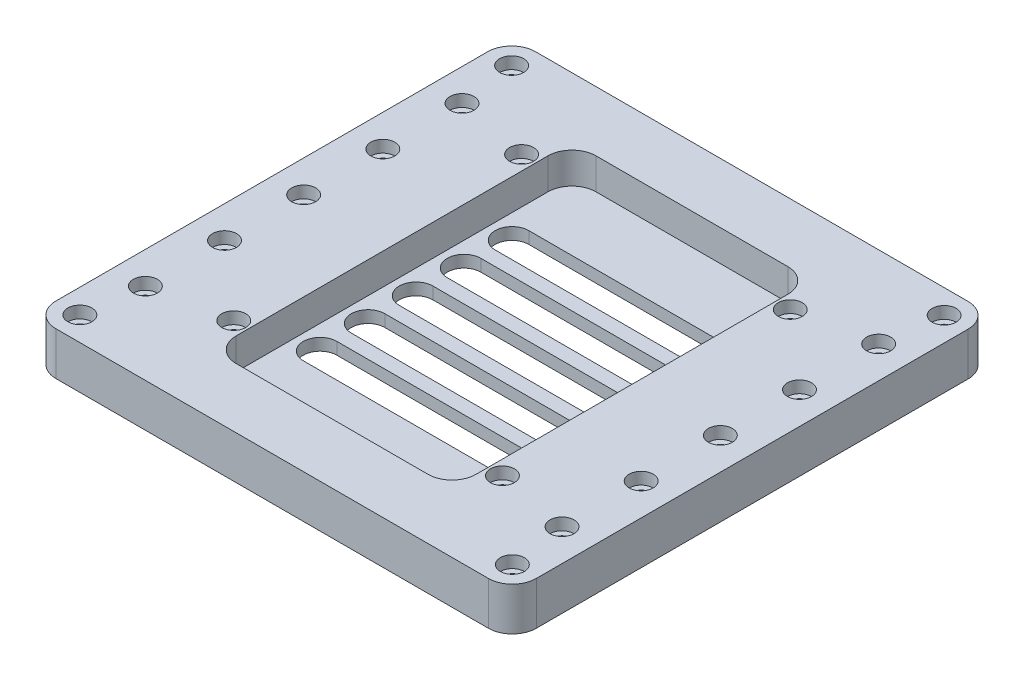
SolidWorks part; units mm, degrees
ref_plane "前视基准面" through (0, 0, 0) normal (0, 0, 1) x (1, 0, 0)
ref_plane "上视基准面" through (0, 0, 0) normal (0, 1, 0) x (1, 0, 0)
ref_plane "右视基准面" through (0, 0, 0) normal (1, 0, 0) x (0, 0, -1)
sketch "Sketch1" plane through (0, 0, 0) normal (0, 1, 0) x (1, 0, 0)
  line L0 (83.75, 0) -> (89.95, 0) construction
  line L1 (-100.15, 100) -> (100.15, 100)
  line L2 (-100.15, 100) -> (-100.15, -100)
  line L3 (-100.15, -100) -> (100.15, -100)
  line L4 (100.15, 100) -> (100.15, -100)
  line L5 (-100.15, 100) -> (100.15, -100) construction
  line L6 (-100.15, -100) -> (100.15, 100) construction
  line L7 (86.85, 75) -> (86.85, -75) construction
  line L8 (0, 0) -> (0, -34.4802) construction
  line L9 (0, 0) -> (-31.4397, 0) construction
  line L10 (56, 60) -> (-56, 60) construction
  line L11 (56, 60) -> (56, -60) construction
  line L12 (56, -60) -> (-56, -60) construction
  line L13 (-56, 60) -> (-56, -60) construction
  line L14 (56, 60) -> (-56, -60) construction
  line L15 (56, -60) -> (-56, 60) construction
  line L16 (100.15, 0) -> (86.85, 0) construction
  line L17 (0, 0) -> (0, 40) construction
  line L18 (0, 40) -> (40, 40) construction
  line L19 (40, 33) -> (-40, 33)
  line L20 (40, 47) -> (-40, 47)
  line L21 (40, 13) -> (-40, 13)
  line L22 (40, 27) -> (-40, 27)
  line L23 (40, -7) -> (-40, -7)
  line L24 (40, 7) -> (-40, 7)
  line L25 (40, -27) -> (-40, -27)
  line L26 (40, -13) -> (-40, -13)
  line L27 (40, -47) -> (-40, -47)
  line L28 (40, -33) -> (-40, -33)
  circle A0 centre (86.85, 0) radius 2.5
  circle A1 centre (86.85, 33) radius 2.5
  circle A2 centre (86.85, 66) radius 2.5
  circle A3 centre (86.85, -66) radius 2.5
  circle A4 centre (86.85, -33) radius 2.5
  circle A5 centre (-86.85, 66) radius 2.5
  circle A6 centre (-86.85, 33) radius 2.5
  circle A7 centre (-86.85, 0) radius 2.5
  circle A8 centre (-86.85, -33) radius 2.5
  circle A9 centre (-86.85, -66) radius 2.5
  circle A10 centre (56, -60) radius 2.5
  circle A11 centre (-56, -60) radius 2.5
  circle A12 centre (-56, 60) radius 2.5
  circle A13 centre (56, 60) radius 2.5
  arc A15 (40, 33) -> (40, 47) centre (40, 40) ccw
  arc A16 (-40, 33) -> (-40, 47) centre (-40, 40) cw
  arc A17 (-40, 13) -> (-40, 27) centre (-40, 20) cw
  arc A18 (40, 13) -> (40, 27) centre (40, 20) ccw
  arc A19 (-40, -7) -> (-40, 7) centre (-40, 0) cw
  arc A20 (40, -7) -> (40, 7) centre (40, 0) ccw
  arc A21 (-40, -27) -> (-40, -13) centre (-40, -20) cw
  arc A22 (40, -27) -> (40, -13) centre (40, -20) ccw
  arc A23 (-40, -47) -> (-40, -33) centre (-40, -40) cw
  arc A24 (40, -47) -> (40, -33) centre (40, -40) ccw
  point P0 (0, 0)
  point P11 (86.85, 0)
  point P50 (0, 33)
  point P52 (0, 47)
  dimension "D3" = 3
  dimension "D6" = 5
  dimension "D7" = 5
  dimension "D11" = 7
  dimension "D1" = 200.3
  dimension "D2" = 200
  dimension "D4" = 112
  dimension "D5" = 120
  dimension "D8" = 13.3
  dimension "D9" = 40
  dimension "D10" = 40
  dimension "D12" = 5
extrude "Boss-Extrude1" add sketch "Sketch1" along normal blind 18
fillet "Fillet1" radius 10 4 edges at (-100.15, 9, 100) (100.15, 9, 100) (-100.15, 9, -100) (100.15, 9, -100)
sketch "Sketch2" plane through (0, 18, 0) normal (0, 1, 0) x (1, 0, 0)
  line L0 (0, 0) -> (0, 100) construction
  line L1 (90.15, 100) -> (-90.15, 100) construction
  line L2 (0, 0) -> (-100.15, 0) construction
  line L3 (-100.15, 90) -> (-100.15, -90) construction
  circle A0 centre (-86.85, 66) radius 5
  circle A1 centre (-86.85, 33) radius 5
  circle A2 centre (-86.85, 0) radius 5
  circle A3 centre (-86.85, -33) radius 5
  circle A4 centre (-86.85, -66) radius 5
  circle A5 centre (86.85, -66) radius 5
  circle A6 centre (86.85, -33) radius 5
  circle A7 centre (86.85, 0) radius 5
  circle A8 centre (86.85, 33) radius 5
  circle A9 centre (86.85, 66) radius 5
  circle A10 centre (-56, 60) radius 5
  circle A11 centre (-56, -60) radius 5
  circle A12 centre (56, -60) radius 5
  circle A13 centre (56, 60) radius 5
  dimension "D1" = 5
  dimension "D2" = 10
  dimension "D3" = 10
  dimension "D4" = 33
extrude "Cut-Extrude1" cut sketch "Sketch2" against normal blind 5
sketch "Sketch3" plane through (0, 18, 0) normal (0, 1, 0) x (1, 0, 0)
  line L1 (-50, 75) -> (50, 75)
  line L2 (-50, 75) -> (-50, -75)
  line L3 (-50, -75) -> (50, -75)
  line L4 (50, 75) -> (50, -75)
  line L5 (-50, 75) -> (50, -75) construction
  line L6 (-50, -75) -> (50, 75) construction
  point P0 (0, 0)
  dimension "D1" = 150
  dimension "D2" = 100
extrude "Cut-Extrude2" cut sketch "Sketch3" against normal blind 13
fillet "Fillet2" radius 10 4 edges at (-50, 11.5, -75) (-50, 11.5, 75) (50, 11.5, 75) (50, 11.5, -75)
sketch "Sketch4" plane through (0, 18, 0) normal (0, 1, 0) x (1, 0, 0)
  circle A0 centre (-90.15, -90) radius 5
  circle A1 centre (-90.15, 90) radius 5
  circle A2 centre (90.15, 90) radius 5
  circle A3 centre (90.15, -90) radius 5
  dimension "D1" = 10
  dimension "D2" = 10
  dimension "D3" = 10
  dimension "D4" = 10
extrude "Cut-Extrude3" cut sketch "Sketch4" against normal blind 5
sketch "Sketch5" plane through (0, 13, 0) normal (0, 1, 0) x (1, 0, 0)
  circle A0 centre (-90.15, -90) radius 2.5
  circle A1 centre (-90.15, 90) radius 2.5
  circle A2 centre (90.15, 90) radius 2.5
  circle A3 centre (90.15, -90) radius 2.5
  dimension "D1" = 5
  dimension "D2" = 5
  dimension "D3" = 5
  dimension "D4" = 5
extrude "Cut-Extrude4" cut sketch "Sketch5" against normal through all
